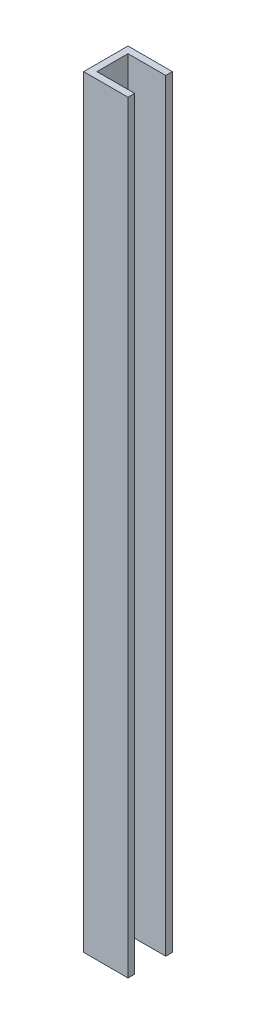
SolidWorks part; units mm, degrees
ref_plane "Front Plane" through (0, 0, 0) normal (0, 0, 1) x (1, 0, 0)
ref_plane "Top Plane" through (0, 0, 0) normal (0, 1, 0) x (1, 0, 0)
ref_plane "Right Plane" through (0, 0, 0) normal (1, 0, 0) x (0, 0, -1)
sketch "Sketch2" plane through (0, 0, 0) normal (0, 1, 0) x (1, 0, 0)
  line L1 (-5, -5) -> (5, -5)
  line L2 (-5, -5) -> (-5, 5)
  line L3 (-5, 5) -> (5, 5)
  line L4 (5, -5) -> (5, 5)
  line L5 (-5, -5) -> (5, 5) construction
  line L6 (-5, 5) -> (5, -5) construction
  line L7 (5, 3.5) -> (-3.5, 3.5)
  line L8 (5, 3.5) -> (5, -3.5)
  line L9 (5, -3.5) -> (-3.5, -3.5)
  line L10 (-3.5, 3.5) -> (-3.5, -3.5)
  point P0 (0, 0)
  dimension "D1" = 1.5
  dimension "D2" = 1.5
  dimension "D3" = 10
extrude "Boss-Extrude1" add sketch "Sketch2" along normal mid plane 172 contours L10 L7 L4 L3 L2 L1 L9
